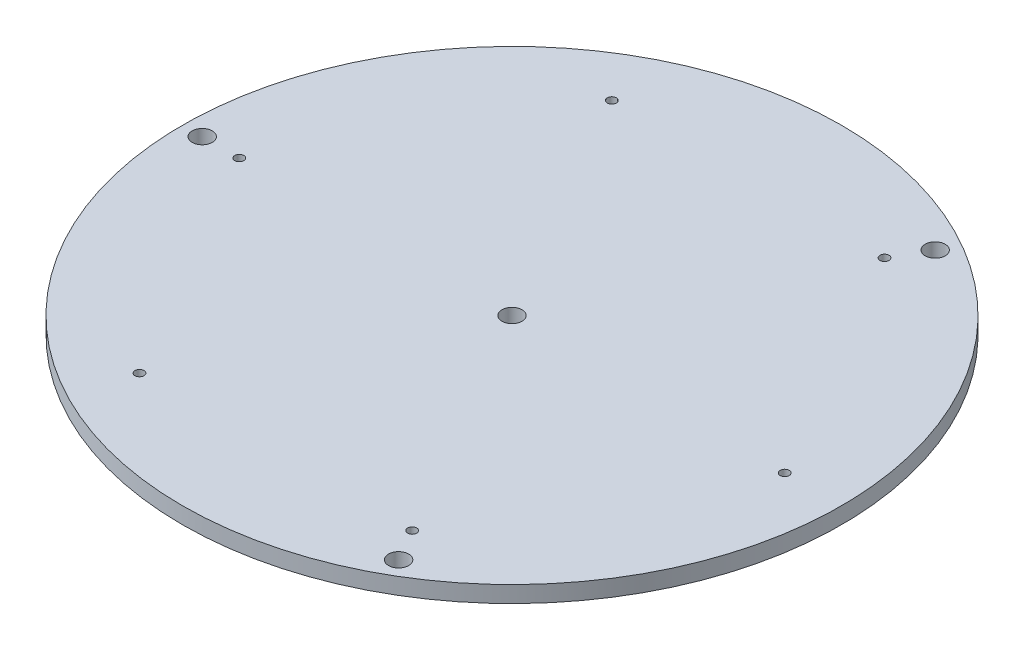
SolidWorks part; units mm, degrees
ref_plane "Спереди" through (0, 0, 0) normal (0, 0, 1) x (1, 0, 0)
ref_plane "Сверху" through (0, 0, 0) normal (0, 1, 0) x (1, 0, 0)
ref_plane "Справа" through (0, 0, 0) normal (1, 0, 0) x (0, 0, -1)
sketch "Эскиз1" plane through (0, 0, 0) normal (0, 1, 0) x (1, 0, 0)
  circle A0 centre (0, 0) radius 200
  circle A1 centre (0, 0) radius 6.1
  dimension "D1" = 400
  dimension "D2" = 12.2
extrude "Бобышка-Вытянуть1" add sketch "Эскиз1" along normal blind 10
sketch "Эскиз2" plane through (0, 10, 0) normal (0, 1, 0) x (1, 0, 0)
  circle A0 centre (0, 0) radius 188 construction
  circle A1 centre (0, 0) radius 200 construction
  circle A2 centre (-188, 0) radius 6.1
  dimension "D1" = 12
  dimension "D2" = 12.2
extrude "Вырез-Вытянуть1" cut sketch "Эскиз2" against normal blind 10
pattern_circular "Круговой массив1" count 3 over 360 about axis through (0, 0, 0) along (0, 1, 0) of "Вырез-Вытянуть1"
sketch "Эскиз3" plane through (0, 10, 0) normal (0, 1, 0) x (1, 0, 0)
  circle A0 centre (0, 0) radius 165.5 construction
  circle A1 centre (-165.5, 0) radius 2.75
  dimension "D1" = 331
  dimension "D2" = 5.5
extrude "Вырез-Вытянуть2" cut sketch "Эскиз3" against normal blind 10
pattern_circular "Круговой массив2" count 6 over 360 about axis through (0, 0, 0) along (0, 1, 0) of "Вырез-Вытянуть2"
